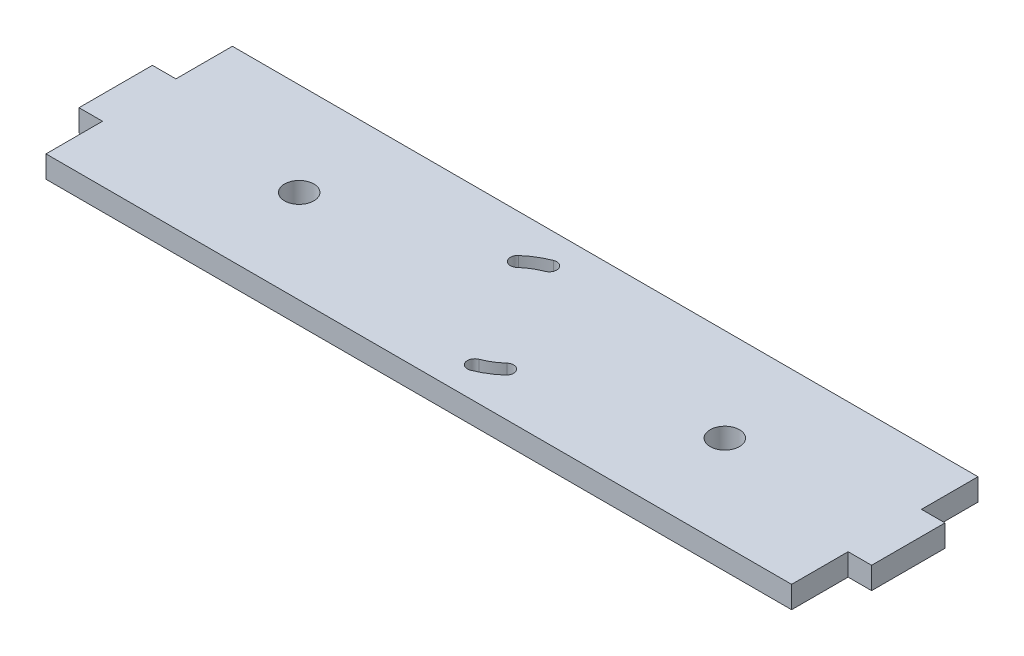
SolidWorks part; units mm, degrees
ref_plane "Front Plane" through (0, 0, 0) normal (0, 0, 1) x (1, 0, 0)
ref_plane "Top Plane" through (0, 0, 0) normal (0, 1, 0) x (1, 0, 0)
ref_plane "Right Plane" through (0, 0, 0) normal (1, 0, 0) x (0, 0, -1)
sketch "Sketch1" plane through (0, 0, 0) normal (0, 1, 0) x (1, 0, 0)
  line L0 (-50.8, -5) -> (-50.8, -12.7)
  line L1 (-50.8, 12.7) -> (50.8, 12.7)
  line L2 (-50.8, 12.7) -> (-50.8, 5)
  line L3 (-50.8, -12.7) -> (50.8, -12.7)
  line L4 (50.8, 12.7) -> (50.8, 5)
  line L5 (50.8, 5) -> (54, 5)
  line L6 (50.8, -5) -> (54, -5)
  line L7 (-54, 5) -> (-50.8, 5)
  line L8 (-54, 5) -> (-54, -5)
  line L9 (-54, -5) -> (-50.8, -5)
  line L10 (54, 5) -> (54, -5)
  line L11 (50.8, -5) -> (50.8, -12.7)
  dimension "D1" = 101.6
  dimension "D2" = 25.4
  dimension "D3" = 10
extrude "Boss-Extrude1" add sketch "Sketch1" along normal blind 3
sketch "Sketch2" plane through (0, 3, 0) normal (0, 1, 0) x (1, 0, 0)
  arc A0 (2.9271, -7.4453) -> (5.2974, -5.9948) centre (0, 0) ccw
  arc A1 (-3.6589, 9.3066) -> (-6.6218, 7.4935) centre (0, 0) ccw
  arc A2 (-2.9271, 7.4453) -> (-5.2974, 5.9948) centre (0, 0) ccw
  arc A3 (2.9271, -7.4453) -> (3.6589, -9.3066) centre (3.293, -8.3759) ccw
  arc A4 (6.6218, -7.4935) -> (5.2974, -5.9948) centre (5.9596, -6.7441) ccw
  arc A5 (3.6589, -9.3066) -> (6.6218, -7.4935) centre (0, 0) ccw
  arc A7 (-6.6218, 7.4935) -> (-5.2974, 5.9948) centre (-5.9596, 6.7441) ccw
  arc A8 (-2.9271, 7.4453) -> (-3.6589, 9.3066) centre (-3.293, 8.3759) ccw
extrude "Cut-Extrude1" cut sketch "Sketch2" against normal through all
sketch "Sketch3" plane through (0, 3, 0) normal (0, 1, 0) x (1, 0, 0)
  line L0 (54, -5) -> (54, 5) construction
  line L1 (-54, 5) -> (-54, -5) construction
  circle A0 centre (29, 0) radius 2
  circle A1 centre (-29, 0) radius 2
  dimension "D1" = 25
  dimension "D2" = 25
extrude "Cut-Extrude2" cut sketch "Sketch3" against normal through all
